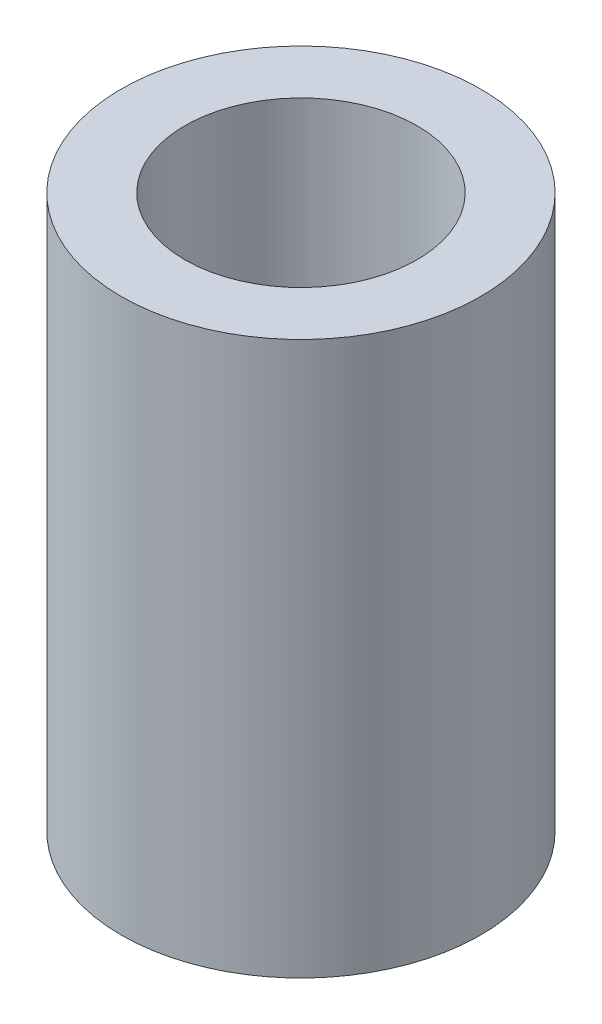
SolidWorks part; units mm, degrees
ref_plane "Front Plane" through (0, 0, 0) normal (0, 0, 1) x (1, 0, 0)
ref_plane "Top Plane" through (0, 0, 0) normal (0, 1, 0) x (1, 0, 0)
ref_plane "Right Plane" through (0, 0, 0) normal (1, 0, 0) x (0, 0, -1)
sketch "Sketch1" plane through (0, 0, 0) normal (0, 1, 0) x (1, 0, 0)
  circle A0 centre (0, 0) radius 2.1
  circle A1 centre (0, 0) radius 3.25
  dimension "D1" = 4.2
  dimension "D2" = 6.5
extrude "Boss-Extrude1" add sketch "Sketch1" along normal blind 10
